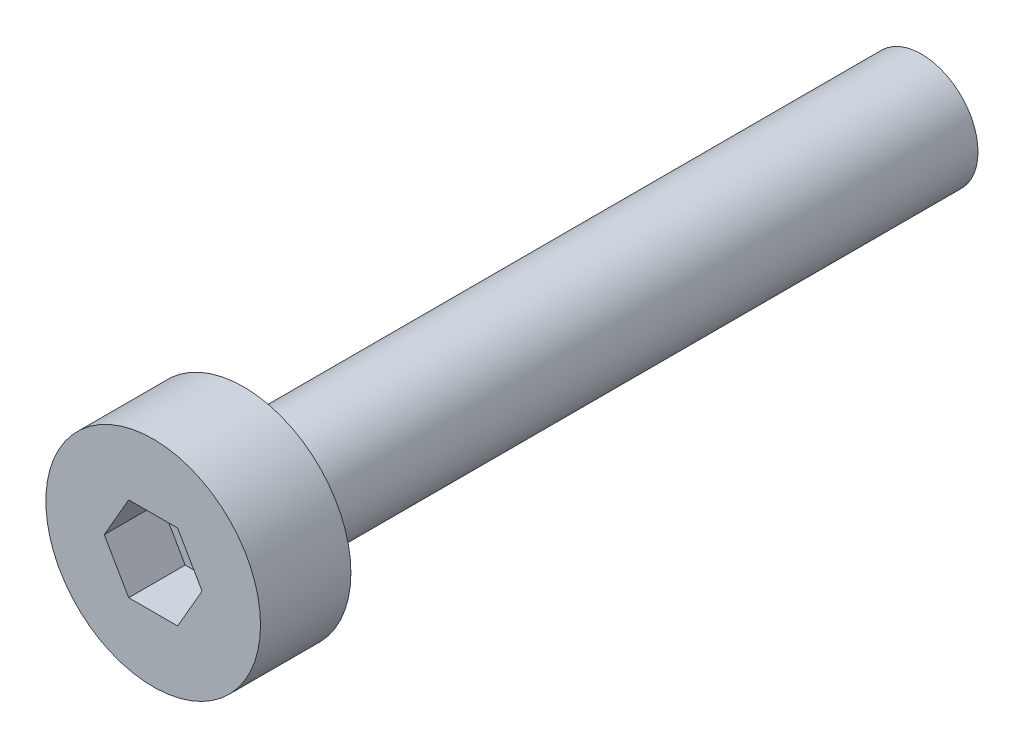
SolidWorks part; units mm, degrees
ref_plane "Plan de face" through (0, 0, 0) normal (0, 0, 1) x (1, 0, 0)
ref_plane "Plan de dessus" through (0, 0, 0) normal (0, 1, 0) x (1, 0, 0)
ref_plane "Plan de droite" through (0, 0, 0) normal (1, 0, 0) x (0, 0, -1)
sketch "Esquisse1" plane through (0, 0, 0) normal (0, 0, 1) x (1, 0, 0)
  circle A0 centre (0, 0) radius 1
  dimension "D1" = 2
extrude "Boss.-Extru.1" add sketch "Esquisse1" along normal blind 12
sketch "Esquisse2" plane through (0, 0, 12) normal (0, 0, 1) x (1, 0, 0)
  circle A0 centre (0, 0) radius 1.9
  dimension "D1" = 3.8
extrude "Boss.-Extru.2" add sketch "Esquisse2" along normal blind 1.6
sketch "Esquisse3" plane through (0, 0, 13.6) normal (0, 0, 1) x (1, 0, 0)
  line L1 (0.866, 0) -> (0.433, 0.75)
  line L2 (0.433, 0.75) -> (-0.433, 0.75)
  line L3 (-0.433, 0.75) -> (-0.866, 0)
  line L4 (-0.866, 0) -> (-0.433, -0.75)
  line L5 (-0.433, -0.75) -> (0.433, -0.75)
  line L6 (0.433, -0.75) -> (0.866, 0)
  circle A0 centre (0, 0) radius 0.75 construction
  dimension "D1" = 1.5
extrude "Enlèv. mat.-Extru.1" cut sketch "Esquisse3" against normal blind 1
